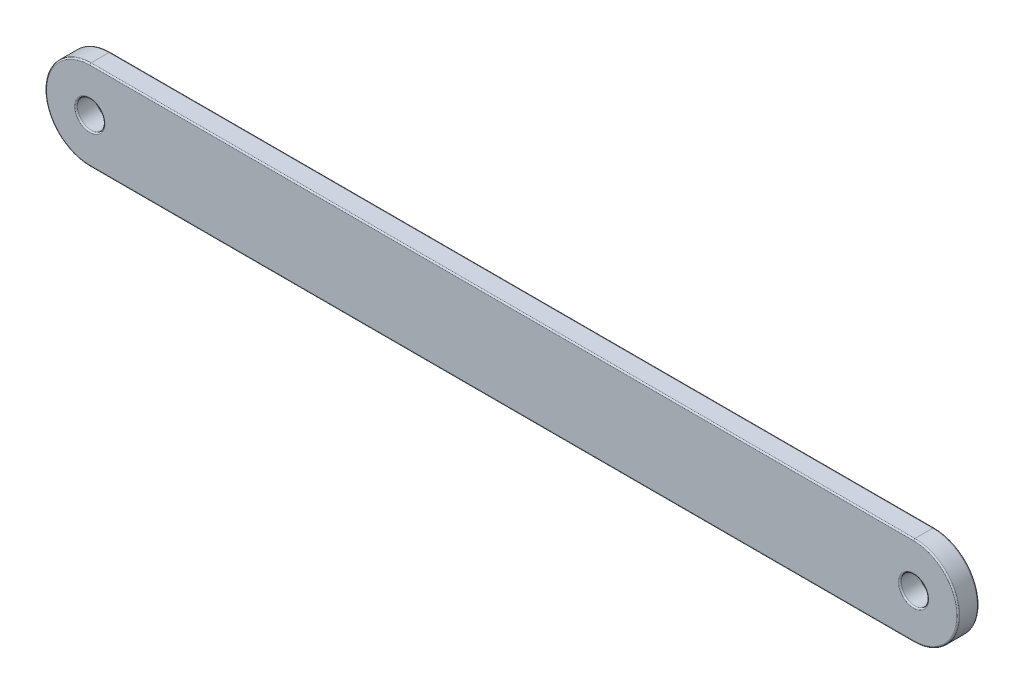
SolidWorks part; units mm, degrees
ref_plane "Front Plane" through (0, 0, 0) normal (0, 0, 1) x (1, 0, 0)
ref_plane "Top Plane" through (0, 0, 0) normal (0, 1, 0) x (1, 0, 0)
ref_plane "Right Plane" through (0, 0, 0) normal (1, 0, 0) x (0, 0, -1)
sketch "Sketch1" plane through (0, 0, 0) normal (0, 0, 1) x (1, 0, 0)
  line L0 (-30, 0) -> (30, 0) construction
  line L1 (-30, 3.25) -> (30, 3.25)
  line L2 (-30, -3.25) -> (30, -3.25)
  arc A0 (-30, 3.25) -> (-30, -3.25) centre (-30, 0) ccw
  arc A1 (30, -3.25) -> (30, 3.25) centre (30, 0) ccw
  circle A2 centre (-30, 0) radius 1
  circle A3 centre (30, 0) radius 1
  point P2 (0, 0)
  dimension "D2" = 3.25
  dimension "D3" = 2
  dimension "D1" = 60
extrude "Boss-Extrude1" add sketch "Sketch1" along normal mid plane 1.5
fillet "Fillet1" radius 0.1 12 edges at (31, 0, -0.75) (31, 0, 0.75) (-29, 0, -0.75) (-29, 0, 0.75) (-33.25, 0, -0.75) (0, -3.25, -0.75) (33.25, 0, -0.75) (-33.25, 0, 0.75) (0, -3.25, 0.75) (33.25, 0, 0.75) (0, 3.25, 0.75) (0, 3.25, -0.75)
